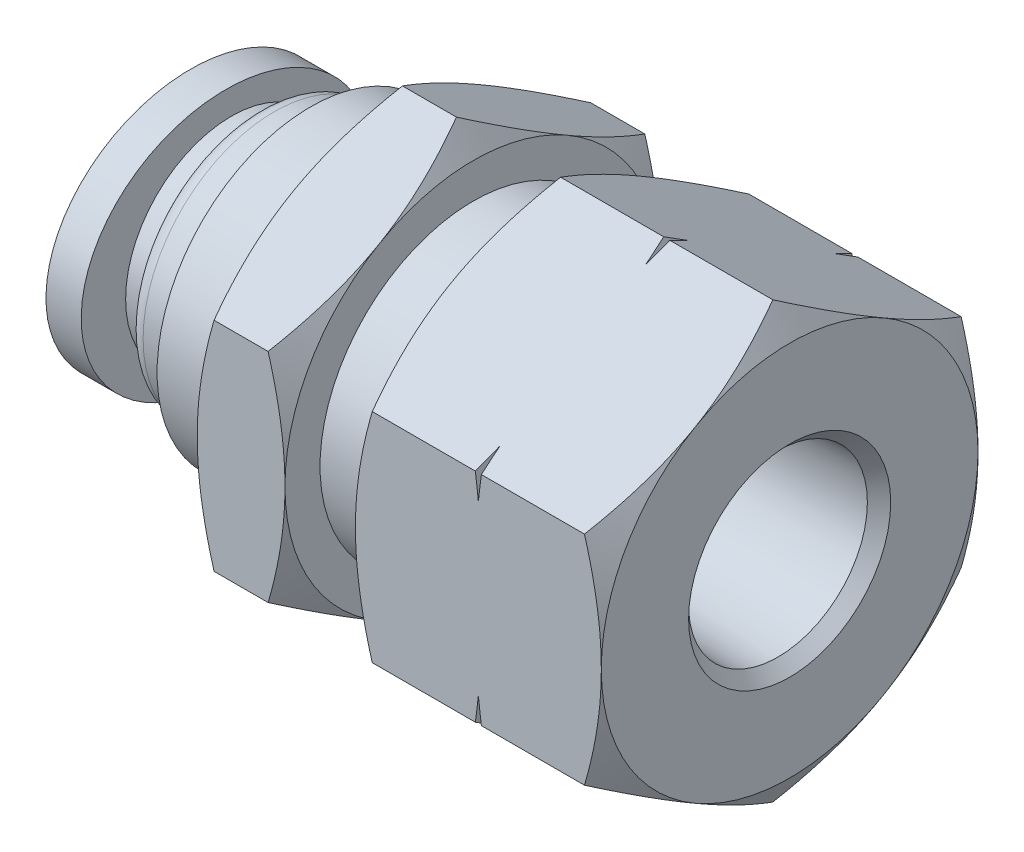
SolidWorks part; units mm, degrees
material "6061-T6 (SS)"
ref_plane "Front Plane" through (0, 0, 0) normal (0, 0, 1) x (1, 0, 0)
ref_plane "Top Plane" through (0, 0, 0) normal (0, 1, 0) x (1, 0, 0)
ref_plane "Right Plane" through (0, 0, 0) normal (1, 0, 0) x (0, 0, -1)
sketch "Sketch1" plane through (0, 0, 0) normal (1, 0, 0) x (0, 0, -1)
  line L1 (0, 9.796) -> (-8.4836, 4.898)
  line L2 (-8.4836, 4.898) -> (-8.4836, -4.898)
  line L3 (-8.4836, -4.898) -> (0, -9.796)
  line L4 (0, -9.796) -> (8.4836, -4.898)
  line L5 (8.4836, -4.898) -> (8.4836, 4.898)
  line L6 (8.4836, 4.898) -> (0, 9.796)
  circle A0 centre (0, 0) radius 8.4836 construction
  dimension "D1" = 16.9672
extrude "Boss-Extrude1" add sketch "Sketch1" along normal mid plane 26.9875
sketch "Sketch2" plane through (0, 0, 0) normal (0, 0, 1) x (1, 0, 0)
  line L0 (13.4937, 0) -> (-13.4937, 0) construction
  line L1 (13.4937, 4.898) -> (13.4937, -4.898) construction
  line L2 (-13.4937, 4.898) -> (-13.4937, -4.898) construction
  line L3 (13.4937, 9.796) -> (13.4937, 8.4836)
  line L4 (13.4937, 9.796) -> (13.4937, 4.898) construction
  line L5 (13.4937, 8.4836) -> (12.736, 9.796)
  line L6 (13.4937, 9.796) -> (-13.4937, 9.796) construction
  line L7 (12.736, 9.796) -> (13.4937, 9.796)
  line L8 (3.1771, 9.796) -> (-1.5134, 9.796)
  line L9 (-1.5134, 9.796) -> (-0.7557, 8.4836)
  line L10 (-0.7557, 8.4836) -> (-0.7557, 6.9024)
  line L11 (-0.7557, 6.9024) -> (2.4193, 6.9024)
  line L12 (2.4193, 6.9024) -> (2.4193, 8.4836)
  line L13 (2.4193, 8.4836) -> (3.1771, 9.796)
  line L14 (7.8204, 9.796) -> (7.9566, 9.288)
  line L15 (7.9566, 9.288) -> (8.0927, 9.796)
  line L16 (8.0927, 9.796) -> (7.8204, 9.796)
  line L17 (-3.9476, 9.796) -> (-4.7053, 8.4836)
  line L18 (-4.7053, 8.4836) -> (-4.7053, 6.9024)
  line L19 (-4.7053, 6.9024) -> (-8.0962, 6.9024)
  line L20 (-8.0962, 6.9024) -> (-8.0962, 5.9055)
  line L21 (-8.0962, 5.9055) -> (-9.7218, 5.9055)
  line L22 (-10.4838, 5.1435) -> (-10.4838, 4.7625)
  line L23 (-10.4838, 4.7625) -> (-11.6522, 4.7625)
  line L24 (-11.6522, 4.7625) -> (-11.6522, 3.81)
  line L25 (-11.6522, 3.81) -> (-13.4937, 3.81)
  line L26 (2.8838, 9.288) -> (13.0293, 9.288) construction
  line L27 (13.4937, 4.0437) -> (4.1973, 3.7401)
  line L28 (4.1973, 3.7401) -> (3.4971, 2.5273)
  line L29 (3.4971, 2.5273) -> (2.2542, 2.5273)
  line L30 (2.2542, 2.5273) -> (2.2542, 3.81)
  line L31 (-13.4937, 0) -> (-13.4937, 3.3147)
  line L32 (-13.4937, 3.3147) -> (-5.8737, 3.3147)
  line L33 (-5.8737, 3.3147) -> (-5.8737, 3.81)
  line L34 (-5.8737, 3.81) -> (2.2542, 3.81)
  line L35 (13.4937, 4.0437) -> (13.4937, 0)
  line L36 (13.4937, 0) -> (-13.4937, 0)
  line L37 (-13.4937, 3.81) -> (-13.4937, 9.796)
  line L38 (-13.4937, 9.796) -> (-3.9476, 9.796)
  arc A0 (-9.7218, 5.9055) -> (-10.4838, 5.1435) centre (-9.7218, 5.1435) ccw
  dimension "D13" = 0.762
  dimension "D1" = 30
  dimension "D2" = 0.508
  dimension "D3" = 60
  dimension "D4" = 11.0744
  dimension "D5" = 16.9672
  dimension "D6" = 13.8049
  dimension "D7" = 3.175
  dimension "D8" = 3.9497
  dimension "D9" = 11.811
  dimension "D10" = 23.9776
  dimension "D11" = 21.59
  dimension "D12" = 9.525
  dimension "D14" = 7.62
  dimension "D15" = 25.146
  dimension "D16" = 1.87
  dimension "D17" = 7.4803
  dimension "D18" = 9.2964
  dimension "D19" = 60
  dimension "D20" = 5.0546
  dimension "D21" = 6.6294
  dimension "D22" = 15.748
  dimension "D23" = 7.62
revolve "Cut-Revolve1" cut sketch "Sketch2" angle 360 about L36
chamfer "Chamfer1" distance 0.508 angle 45 1 edges at (13.4937, 0, -4.0437)
sketch "Sketch3" plane through (-13.4937, 0, 0) normal (-1, 0, 0) x (0, 0, 1)
  circle A0 centre (0, 0) radius 3.3147 construction
  circle A1 centre (0, 0) radius 3.3147
  ellipse E0 centre (0, 0) end of major axis (-6.5088, 0) minor radius 5.6769
  dimension "D1" = 13.0175
  dimension "D2" = 11.3538
extrude "Boss-Extrude2" add sketch "Sketch3" against normal blind 1.5875
